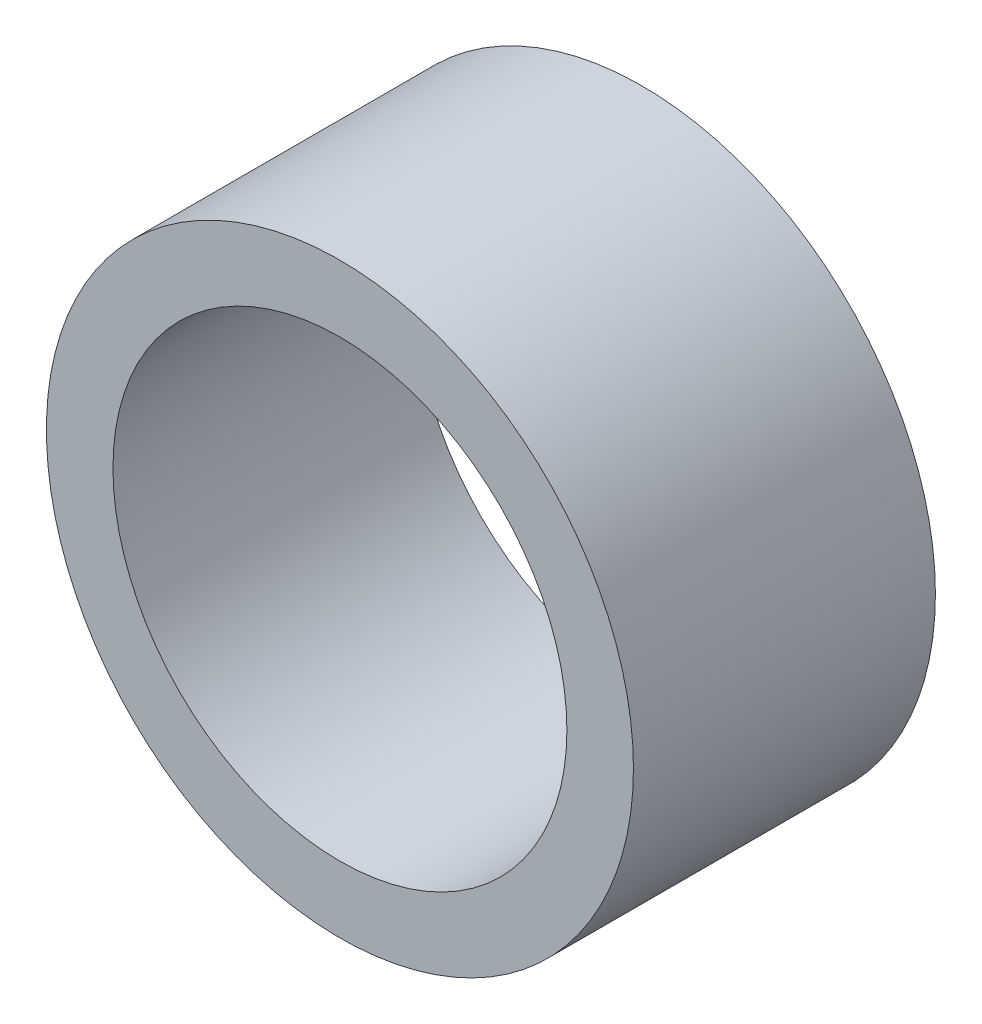
SolidWorks part; units mm, degrees
material "Nylon 101"
ref_plane "Front Plane" through (0, 0, 0) normal (0, 0, 1) x (1, 0, 0)
ref_plane "Top Plane" through (0, 0, 0) normal (0, 1, 0) x (1, 0, 0)
ref_plane "Right Plane" through (0, 0, 0) normal (1, 0, 0) x (0, 0, -1)
sketch "Sketch1" plane through (0, 0, 0) normal (0, 0, 1) x (1, 0, 0)
  circle A0 centre (0, 0) radius 9.525
  circle A1 centre (0, 0) radius 7.366
  dimension "D1" = 19.05
  dimension "D2" = 14.732
extrude "Boss-Extrude1" add sketch "Sketch1" along normal mid plane 9.7998
equation "\"D1@Boss-Extrude1\"=0.0625in+0.45mm/2"
